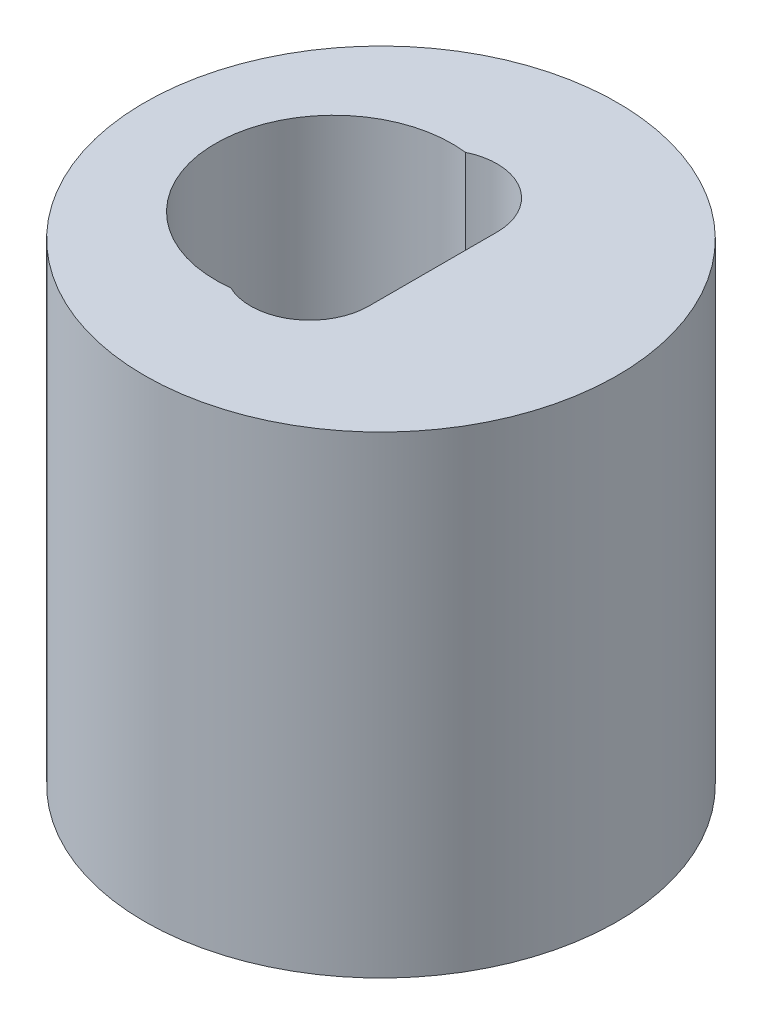
SolidWorks part; units mm, degrees
ref_plane "Front Plane" through (0, 0, 0) normal (0, 0, 1) x (1, 0, 0)
ref_plane "Top Plane" through (0, 0, 0) normal (0, 1, 0) x (1, 0, 0)
ref_plane "Right Plane" through (0, 0, 0) normal (1, 0, 0) x (0, 0, -1)
sketch "Sketch1" plane through (0, 0, 0) normal (0, 1, 0) x (1, 0, 0)
  line L0 (1.397, 1.7227) -> (1.397, -1.7227)
  circle A0 centre (0, 0) radius 6.35
  arc A1 (1.397, 1.7227) -> (1.397, -1.7227) centre (-1.27, 0) ccw
  point P6 (-4.445, 0)
  dimension "D1" = 1.27
  dimension "D2" = 12.7
  dimension "D3" = 3.175
  dimension "D5" = 5.842
extrude "Boss-Extrude1" add sketch "Sketch1" along normal blind 12.7
sketch "Sketch2" plane through (0, 12.7, 0) normal (0, 1, 0) x (1, 0, 0)
  line L0 (1.397, -1.7227) -> (1.397, 1.7227) construction
  line L1 (0, 0) -> (1.397, 0) construction
  line L2 (-0.8828, 3.1513) -> (-0.8828, -3.1513)
  line L3 (1.397, 1.7227) -> (1.397, -1.7227)
  arc A0 (-0.8828, 3.1513) -> (1.397, 1.7227) centre (-0.1905, 1.7227) cw
  arc A1 (1.397, 1.7227) -> (1.397, -1.7227) centre (-1.27, 0) ccw construction
  arc A2 (-0.8828, -3.1513) -> (1.397, -1.7227) centre (-0.1905, -1.7227) ccw
  dimension "D1" = 1.5875
extrude "Cut-Extrude1" cut sketch "Sketch2" against normal through all
